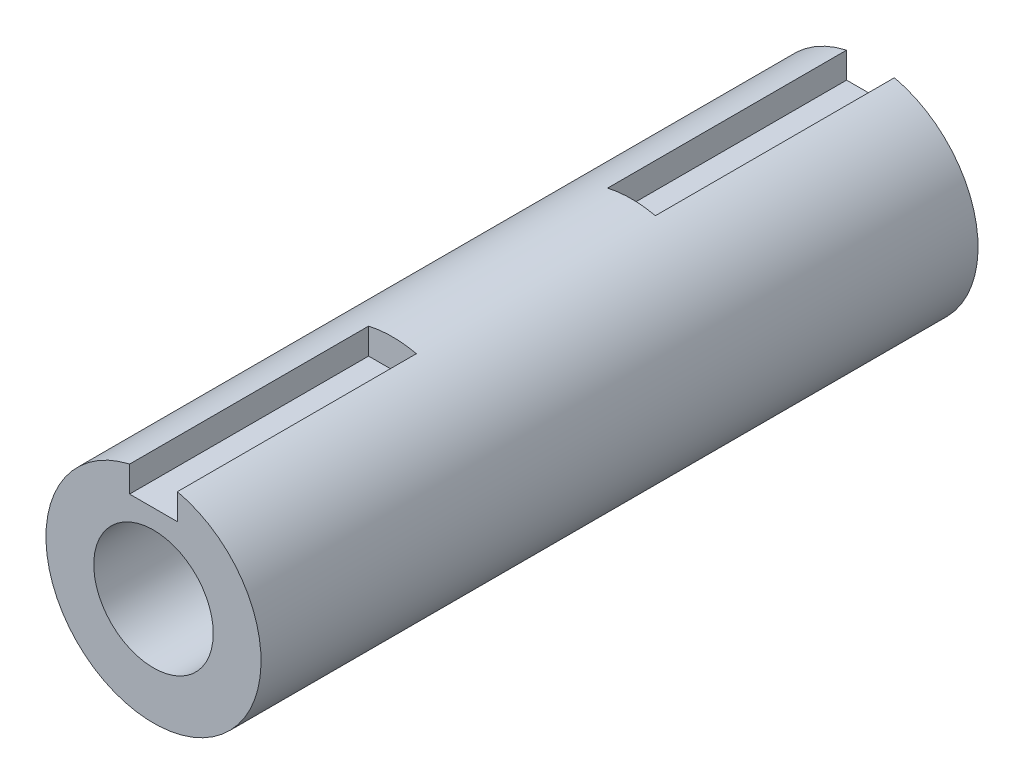
SolidWorks part; units mm, degrees
material "Plain Carbon Steel"
ref_plane "Front Plane" through (0, 0, 0) normal (0, 0, 1) x (1, 0, 0)
ref_plane "Top Plane" through (0, 0, 0) normal (0, 1, 0) x (1, 0, 0)
ref_plane "Right Plane" through (0, 0, 0) normal (1, 0, 0) x (0, 0, -1)
sketch "Sketch1" plane through (0, 0, 0) normal (0, 0, 1) x (1, 0, 0)
  circle A0 centre (0, 0) radius 12.5
  circle A1 centre (0, 0) radius 22.5
  dimension "D1" = 45
  dimension "D2" = 25
extrude "Boss-Extrude1" add sketch "Sketch1" along normal mid plane 150
sketch "Sketch2" plane through (0, 0, 75) normal (0, 0, 1) x (1, 0, 0)
  line L0 (0, 0) -> (0, 16.5) construction
  line L1 (-5, 35.9248) -> (5, 35.9248)
  line L2 (-5, 35.9248) -> (-5, 16.5)
  line L3 (-5, 16.5) -> (5, 16.5)
  line L4 (5, 35.9248) -> (5, 16.5)
  circle A0 centre (0, 0) radius 22.5 construction
  circle A1 centre (0, 0) radius 22.5 construction
  dimension "D3" = 6
  dimension "D1" = 10
  dimension "D2" = 16.5
extrude "Cut-Extrude1" cut sketch "Sketch2" against normal blind 50
mirror "Mirror1" about plane through (0, 0, 0) normal (0, 0, 1) of "Cut-Extrude1"
